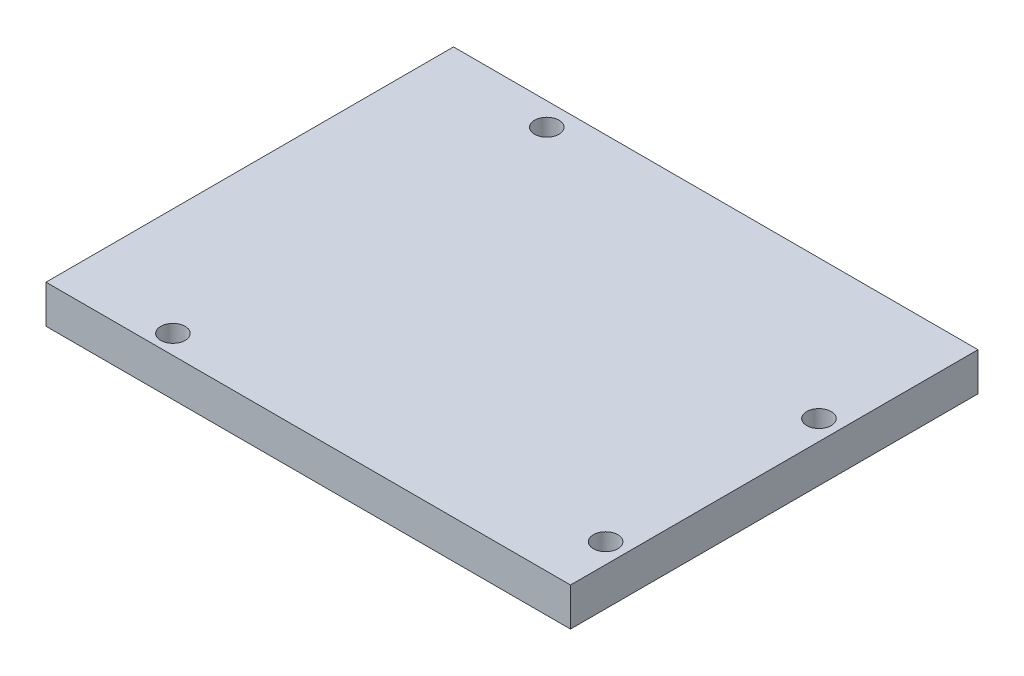
SolidWorks part; units mm, degrees
ref_plane "Alzado" through (0, 0, 0) normal (0, 0, 1) x (1, 0, 0)
ref_plane "Planta" through (0, 0, 0) normal (0, 1, 0) x (1, 0, 0)
ref_plane "Vista lateral" through (0, 0, 0) normal (1, 0, 0) x (0, 0, -1)
sketch "Croquis1" plane through (0, 0, 0) normal (0, 1, 0) x (1, 0, 0)
  line L0 (-35.5277, -25.6269) -> (33.0723, -25.6269)
  line L1 (-35.5277, -25.6269) -> (-35.5277, 27.6731)
  line L2 (-35.5277, 27.6731) -> (33.0723, 27.6731)
  line L3 (33.0723, -25.6269) -> (33.0723, 27.6731)
  circle A0 centre (30.4723, -18.4269) radius 1.6
  circle A1 centre (30.4723, 9.4731) radius 1.6
  circle A2 centre (-20.3277, 24.6731) radius 1.6
  circle A3 centre (-21.4277, -23.1269) radius 1.6
extrude "Saliente-Extruir1" add sketch "Croquis1" along normal blind 5
